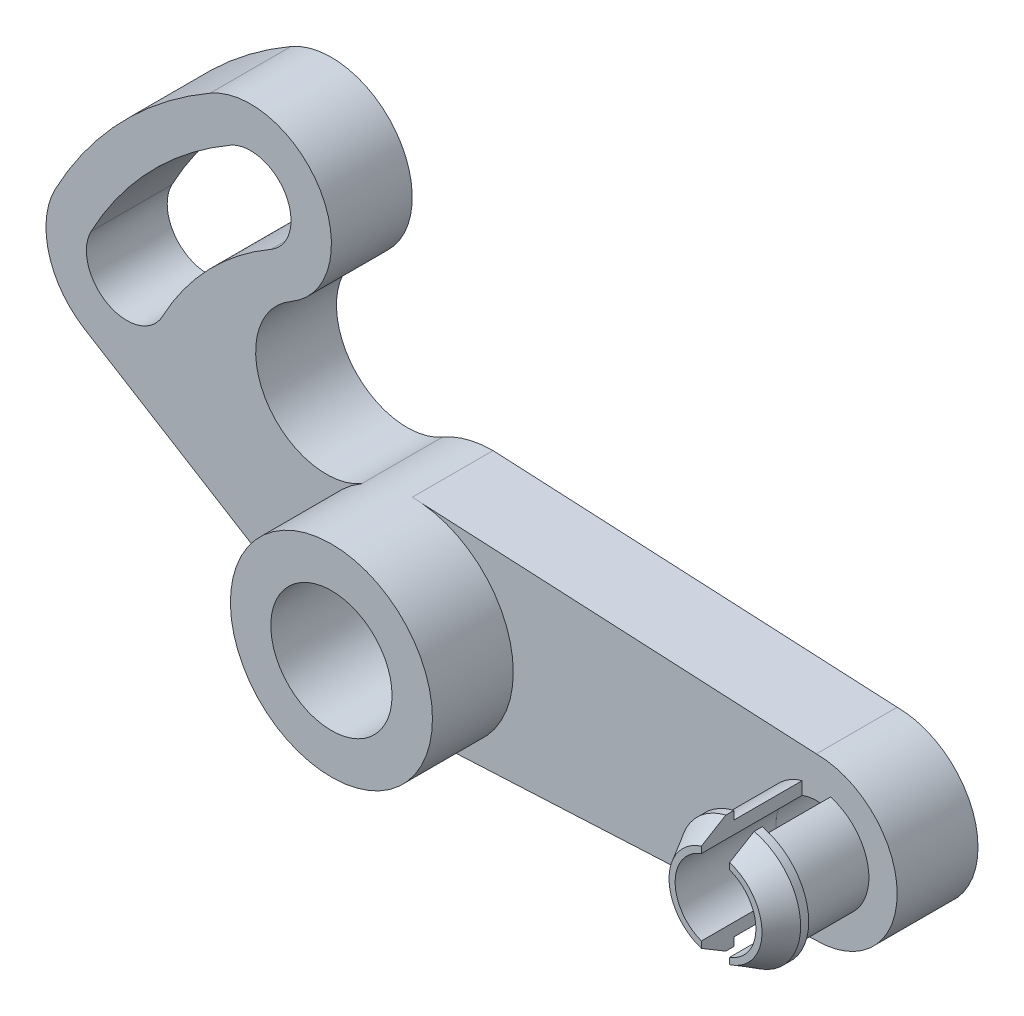
SolidWorks part; units mm, degrees
ref_plane "Plan de face" through (0, 0, 0) normal (0, 0, 1) x (1, 0, 0)
ref_plane "Plan de dessus" through (0, 0, 0) normal (0, 1, 0) x (1, 0, 0)
ref_plane "Plan de droite" through (0, 0, 0) normal (1, 0, 0) x (0, 0, -1)
sketch "Esquisse1" plane through (0, 0, 0) normal (0, 0, 1) x (1, 0, 0)
  line L0 (0, 0) -> (100, 0) construction
  line L1 (0, -25) -> (100, -20)
  line L2 (0, 25) -> (100, 20)
  line L3 (0, 0) -> (-206.3832, 0) construction
  line L4 (0, 0) -> (-204.179, 108.5639) construction
  line L5 (-79.4653, 42.2524) -> (-61.8063, 32.863) construction
  line L6 (0, 0) -> (-12.5, -21.6506) construction
  line L7 (-81.1085, 20.5189) -> (-12.5, -21.6506)
  line L8 (0, 0) -> (-7.5, 12.9904) construction
  line L9 (-45, 77.9423) -> (-35, 60.6218) construction
  line L10 (-35, 60.6218) -> (-74.2257, 128.5627) construction
  line L11 (-12.5, 21.6506) -> (-30, 51.9615) construction
  circle A0 centre (0, 0) radius 15
  arc A1 (0, 25) -> (-12.5, 21.6506) centre (0, 0) ccw
  arc A2 (100, -20) -> (100, 20) centre (100, 0) ccw
  circle A3 centre (100, 0) radius 10
  arc A4 (-70.6358, 37.5577) -> (-40, 69.282) centre (0, 0) cw construction
  arc A5 (-50, 86.6025) -> (-88.2948, 46.9472) centre (0, 0) ccw
  arc A6 (-70.6358, 37.5577) -> (-40, 69.282) centre (0, 0) cw construction
  arc A7 (-45, 77.9423) -> (-79.4653, 42.2524) centre (0, 0) ccw
  arc A8 (-35, 60.6218) -> (-61.8063, 32.863) centre (0, 0) ccw
  arc A9 (-35, 60.6218) -> (-45, 77.9423) centre (-40, 69.282) ccw
  arc A10 (-79.4653, 42.2524) -> (-61.8063, 32.863) centre (-70.6358, 37.5577) ccw
  arc A12 (-30, 51.9615) -> (-50, 86.6025) centre (-40, 69.282) ccw
  arc A13 (-88.2948, 46.9472) -> (-81.1085, 20.5189) centre (-70.6358, 37.5577) ccw
  arc A14 (-30, 51.9615) -> (-12.5, 21.6506) centre (-21.25, 36.8061) ccw
  arc A15 (-12.5, -21.6506) -> (0, -25) centre (0, 0) ccw
  point P12 (-57.5472, 55.5727)
  point P15 (-57.5472, 55.5727)
  dimension "D1" = 50
  dimension "D2" = 30
  dimension "D3" = 40
  dimension "D5" = 20
  dimension "D6" = 70
  dimension "D7" = 90
  dimension "D9" = 100
  dimension "D10" = 0
  dimension "D11" = 0
  dimension "D14" = 32
  dimension "D4" = 100
  dimension "D12" = 28
  dimension "D13" = 60
extrude "Boss.-Extru.1" add sketch "Esquisse1" along normal blind 20
sketch "Esquisse2" plane through (0, 0, 20) normal (0, 0, 1) x (1, 0, 0)
  circle A0 centre (0, 0) radius 15 construction
  circle A1 centre (0, 0) radius 15
  circle A2 centre (0, 0) radius 25
  dimension "D1" = 50
extrude "Boss.-Extru.2" add sketch "Esquisse2" along normal blind 20
chamfer "Chanfrein1" distance 2 angle 45 1 edges at (15, 0, 0)
ref_plane "Plan1" through (100, 0, 0) normal (1, 0, 0) x (0, 0, -1)
sketch "Esquisse5" plane through (100, 0, 0) normal (1, 0, 0) x (0, 0, -1)
  line L0 (0, 0) -> (-64.1916, 0) construction
  line L1 (-20, 0) -> (-20, 10) construction
  line L3 (-20, 10) -> (-44.9538, 10)
  line L4 (-44.9538, 10) -> (-44.9538, 11.5)
  line L5 (-20, 10) -> (-20, 13)
  line L6 (-36.8916, 15) -> (-36.8916, 13)
  line L7 (-36.8916, 13) -> (-20, 13)
  line L8 (-36.8916, 15) -> (-38.8916, 15)
  line L9 (-38.8916, 15) -> (-44.9538, 11.5)
  line L12 (-20, 20) -> (-20, -20) construction
  point P7 (0, 0)
  dimension "D1" = 10
  dimension "D2" = 2
  dimension "D3" = 2
  dimension "D4" = 3
  dimension "D5" = 1.5
  dimension "D6" = 30
revolve "Révolution3" add sketch "Esquisse5" angle 360 about L0
sketch "Esquisse6" plane through (0, 0, 44.9538) normal (0, 0, 1) x (1, 0, 0)
  line L1 (96.5, 16.0146) -> (103.5, 16.0146)
  line L2 (96.5, 16.0146) -> (96.5, -18.3406)
  line L3 (96.5, -18.3406) -> (103.5, -18.3406)
  line L4 (103.5, 16.0146) -> (103.5, -18.3406)
  line L5 (100, 0) -> (100, 21.109) construction
  line L6 (100, -24.7434) -> (100, 24.7434) construction
  point P5 (100, 16.0146)
  dimension "D1" = 7
extrude "Enlèv. mat.-Extru.2" cut sketch "Esquisse6" against normal blind 25
